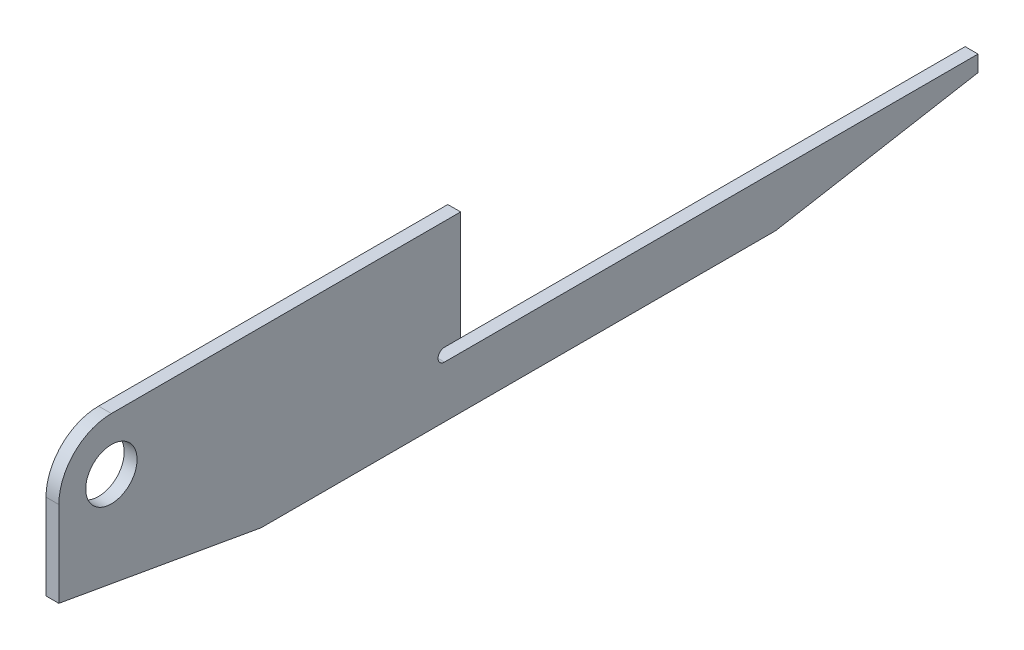
SolidWorks part; units mm, degrees
ref_plane "Front Plane" through (0, 0, 0) normal (1, 0, 0) x (0, 1, 0)
ref_plane "Top Plane" through (0, 0, 0) normal (0, 0, 1) x (0, 1, 0)
ref_plane "Right Plane" through (0, 0, 0) normal (0, 1, 0) x (-1, 0, 0)
sketch "Sketch1" plane through (0, 0, 0) normal (1, 0, 0) x (0, 1, 0)
  line L0 (0, 0) -> (0, -52.1612) construction
  line L1 (-138.9, 0) -> (-138.9, -43.2)
  line L4 (-155.9875, 6.5) -> (-145.4, 6.5)
  line L5 (-152.4, -43.2) -> (-152.4, 6.5) construction
  line L6 (-138.9, -43.2) -> (-152.4, -43.2)
  line L7 (-152.4, -43.2) -> (-152.4, -41.2)
  line L8 (-153.9875, -41.2) -> (-153.9875, -107.2)
  line L9 (-153.9875, -107.2) -> (-155.9875, -107.2)
  line L10 (-155.9875, -107.2) -> (-160.4, -82.1755)
  line L12 (-160.4, -82.1755) -> (-160.4, -18.5245)
  line L13 (-160.4, -18.5245) -> (-155.9875, 6.5)
  circle A0 centre (-145.4, 0) radius 3.175
  arc A1 (-145.4, 6.5) -> (-138.9, 0) centre (-145.4, 0) cw
  arc A2 (-152.4, -41.2) -> (-153.9875, -41.2) centre (-153.1937, -41.2) ccw
  point P9 (-160.9818, -54.1999)
  point P15 (-163.517, -54.6949)
  point P19 (0, 0)
  point P20 (-163.9385, -54.9759)
  point P21 (-172.9305, -55.1179)
  point P23 (0, 0)
  point P24 (-160.4, -3.9781)
  point P25 (-160.4, -12.7826)
  point P26 (0, 0)
  point P27 (-153.1937, 8.4115)
  point P28 (-157.0952, -61.8961)
  point P29 (0, 0)
  point P30 (-155.6107, 6.5)
  point P31 (-122.4457, -3.0913)
  dimension "D1" = 6.35
  dimension "D2" = 6.5
  dimension "D6" = 2
  dimension "D3" = 152.4
  dimension "D5" = 1.5875
  dimension "D7" = 43.2
  dimension "D8" = 10
  dimension "D9" = 64
  dimension "D10" = 8
  dimension "D11" = 2
  dimension "D12" = 7
extrude "Boss-Extrude1" add sketch "Sketch1" along normal mid plane 1.5875
